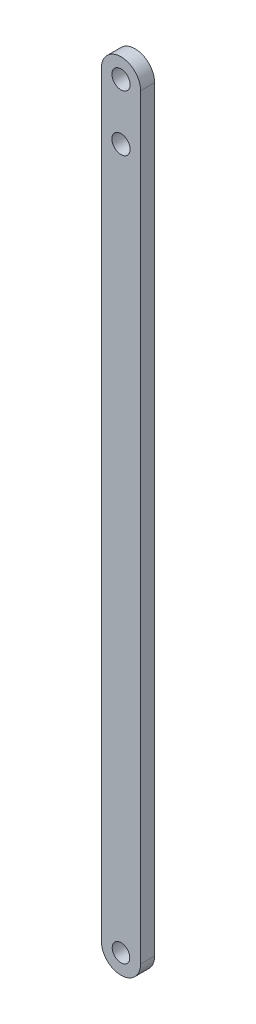
SolidWorks part; units mm, degrees
ref_plane "Front Plane" through (0, 0, 0) normal (0, 0, 1) x (1, 0, 0)
ref_plane "Top Plane" through (0, 0, 0) normal (0, 1, 0) x (1, 0, 0)
ref_plane "Right Plane" through (0, 0, 0) normal (1, 0, 0) x (0, 0, -1)
sketch "Sketch1" plane through (0, 0, 0) normal (0, 0, 1) x (1, 0, 0)
  line L0 (0, 270) -> (0, 0) construction
  line L1 (7, 270) -> (7, 0)
  line L2 (-7, 270) -> (-7, 0)
  arc A1 (7, 270) -> (-7, 270) centre (0, 270) ccw
  circle A2 centre (0, 0) radius 3.1306
  arc A3 (-7, 0) -> (7, 0) centre (0, 0) ccw
  dimension "D1" = 270
  dimension "D3" = 7
  dimension "D2" = 14
extrude "Boss-Extrude1" add sketch "Sketch1" along normal blind 5
sketch "Sketch2" plane through (0, 0, 5) normal (0, 0, 1) x (1, 0, 0)
  line L0 (0, 270) -> (0, 250) construction
  circle A0 centre (0, 270) radius 3.25
  circle A1 centre (0, 250) radius 3.25
extrude "Cut-Extrude1" cut sketch "Sketch2" against normal blind 10
